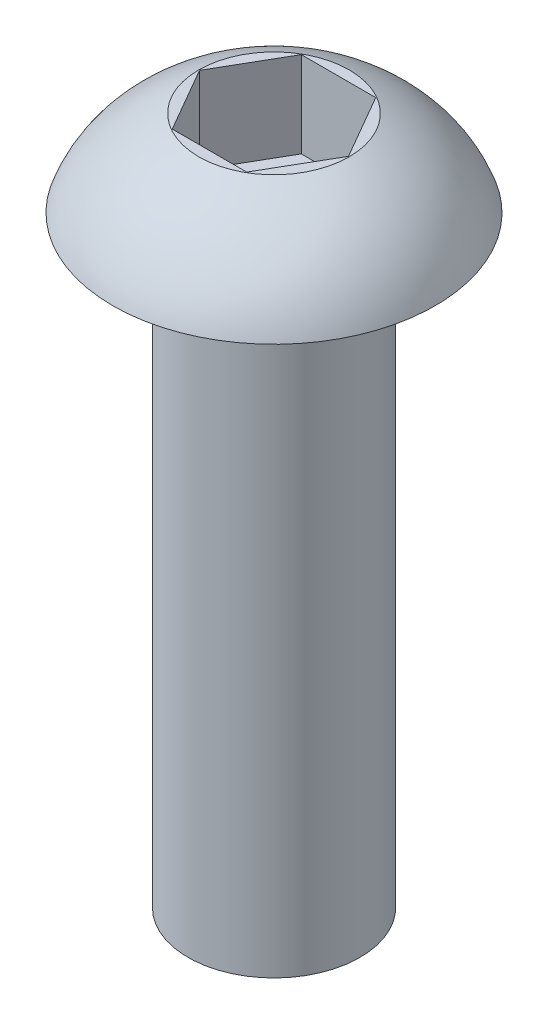
SolidWorks part; units mm, degrees
ref_plane "前视基准面" through (0, 0, 0) normal (0, 0, 1) x (1, 0, 0)
ref_plane "上视基准面" through (0, 0, 0) normal (0, 1, 0) x (1, 0, 0)
ref_plane "右视基准面" through (0, 0, 0) normal (1, 0, 0) x (0, 0, -1)
other "Configuration Table"
sketch "Sketch15" plane through (0, 0, 0) normal (1, 0, 0) x (0, 0, -1)
  line L0 (-1, -7) -> (-1, 7)
  line L1 (-1, 7) -> (1, 7)
  line L2 (-1, 7) -> (-1, -7)
  line L3 (-1, -7) -> (1, -7)
  line L4 (1, 7) -> (1, -7)
  line L5 (-1, 7) -> (1, -7) construction
  line L6 (-1, -7) -> (1, 7) construction
  line L7 (1, 7) -> (2.75, 7)
  line L8 (-1, 7) -> (0.75, 7)
  line L9 (0.75, 7) -> (0.75, 9)
  spline S0 degree 2 poles (0.75, 9) (2.291, 8.3196) (2.75, 7) knots 0 0 0 0.856056 0.856056 0.856056
  point P0 (0, 0)
  dimension "D1" = 14
  dimension "D2" = 2
  dimension "D3" = 3.75
  dimension "D4" = 1.75
  dimension "D5" = 2
revolve "Revolve3" add sketch "Sketch15" angle 360 about L0
ref_plane "Plane4" through (0, 7, 0) normal (0, 1, 0) x (1, 0, 0)
sketch "Sketch19" plane through (0, 7, 0) normal (0, 1, 0) x (1, 0, 0)
  line L1 (1.7321, -1) -> (0.866, 0.5)
  line L2 (0.866, 0.5) -> (-0.866, 0.5)
  line L3 (-0.866, 0.5) -> (-1.7321, -1)
  line L4 (-1.7321, -1) -> (-0.866, -2.5)
  line L5 (-0.866, -2.5) -> (0.866, -2.5)
  line L6 (0.866, -2.5) -> (1.7321, -1)
  circle A0 centre (0, -1) radius 1.5 construction
  circle A1 centre (0, -1) radius 1.75
  dimension "D1" = 3
extrude "Boss-Extrude11" add sketch "Sketch19" along normal blind 2
